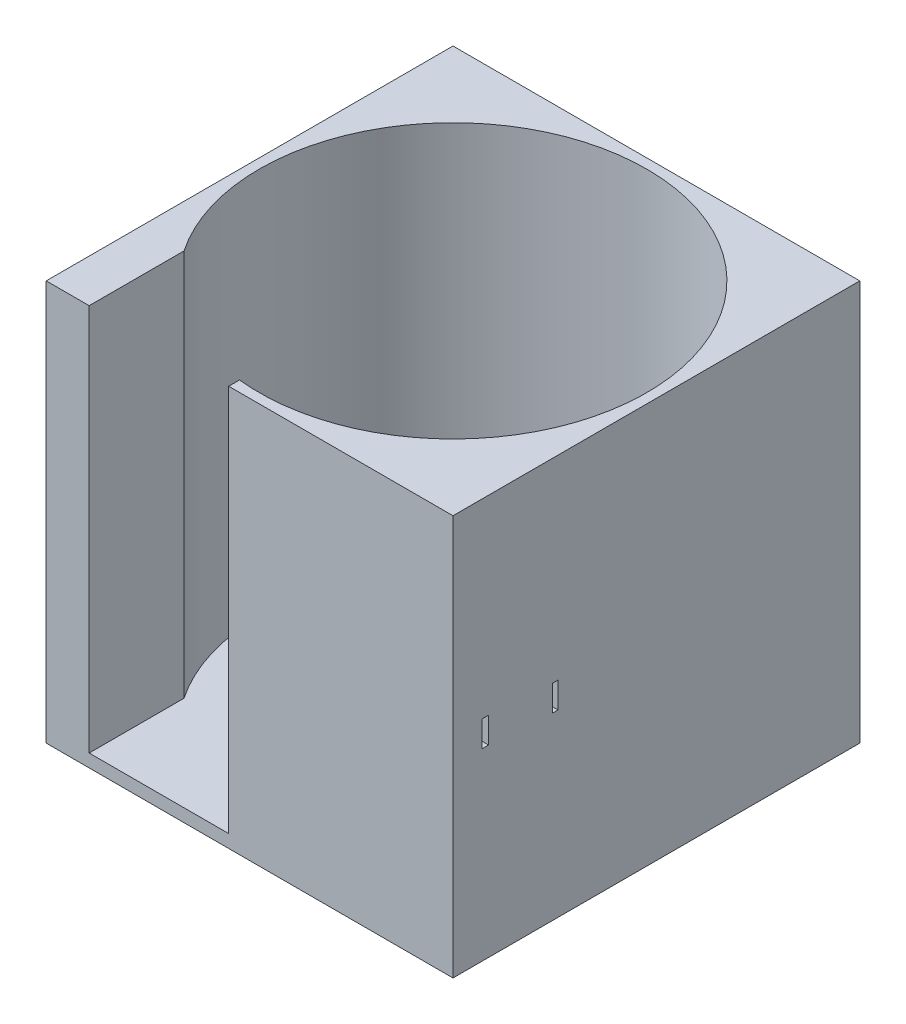
SolidWorks part; units mm, degrees
ref_plane "Front Plane" through (0, 0, 0) normal (0, 0, 1) x (1, 0, 0)
ref_plane "Top Plane" through (0, 0, 0) normal (0, 1, 0) x (1, 0, 0)
ref_plane "Right Plane" through (0, 0, 0) normal (1, 0, 0) x (0, 0, -1)
sketch "Sketch1" plane through (0, 0, 0) normal (0, 1, 0) x (1, 0, 0)
  line L1 (-31.5, -31.5) -> (31.5, -31.5)
  line L2 (-31.5, -31.5) -> (-31.5, 31.5)
  line L3 (-31.5, 31.5) -> (31.5, 31.5)
  line L4 (31.5, -31.5) -> (31.5, 31.5)
  line L5 (-31.5, -31.5) -> (31.5, 31.5) construction
  line L6 (-31.5, 31.5) -> (31.5, -31.5) construction
  point P0 (0, 0)
  dimension "D1" = 63
  dimension "D2" = 63
extrude "Boss-Extrude1" add sketch "Sketch1" along normal blind 62
sketch "Sketch2" plane through (0, 62, 0) normal (0, 1, 0) x (1, 0, 0)
  circle A0 centre (0, 0) radius 30
  dimension "D1" = 60
extrude "Cut-Extrude1" cut sketch "Sketch2" against normal blind 60
sketch "Sketch4" plane through (0, 2, 0) normal (0, 1, 0) x (1, 0, 0)
  circle A0 centre (0, 0) radius 5
  dimension "D1" = 10
extrude "Cut-Extrude2" cut sketch "Sketch4" against normal through all
sketch "Sketch17" plane through (0, 62, 0) normal (0, 1, 0) x (1, 0, 0)
  line L0 (-31.5, -31.5) -> (31.5, -31.5) construction
  line L1 (-3.235, -31.5) -> (-24.8473, -31.5)
  line L2 (-3.235, -31.5) -> (-3.235, -16.811)
  line L3 (-3.235, -16.811) -> (-24.8473, -16.811)
  line L4 (-24.8473, -31.5) -> (-24.8473, -16.811)
  circle A0 centre (0, 0) radius 30 construction
extrude "Cut-Extrude10" cut sketch "Sketch17" against normal blind 60
sketch "Sketch7" plane through (0, 2, 0) normal (0, 1, 0) x (1, 0, 0)
  text T0 "Evening" font "@Microsoft YaHei UI" height 3.5
sketch "Sketch9" plane through (0, 2, 0) normal (0, 1, 0) x (1, 0, 0)
  text T0 "Morning" font "@Microsoft YaHei" height 3.5
extrude "Cut-Extrude5" cut sketch "Sketch9" against normal blind 0.5
sketch "Sketch8" plane through (0, 2, 0) normal (0, 1, 0) x (1, 0, 0)
  text T0 "Noon" font "@Microsoft YaHei" height 3.5
extrude "Cut-Extrude6" cut sketch "Sketch8" against normal blind 0.5
extrude "Cut-Extrude7" cut sketch "Sketch7" against normal blind 0.5
sketch "Sketch19" plane through (31.5, 0, 0) normal (1, 0, 0) x (0, 0, -1)
  line L0 (-31.5, 0) -> (-16, 0) construction
  line L1 (-31.5, 0) -> (31.5, 0) construction
  line L4 (-16.1198, 31.8299) -> (-15.25, 31.8299)
  line L5 (-16.1198, 31.8299) -> (-16.1198, 27.8299)
  line L6 (-16.1198, 27.8299) -> (-15.25, 27.8299)
  line L7 (-15.25, 31.8299) -> (-15.25, 27.8299)
  line L8 (-16.1198, 31.8299) -> (-15.25, 27.8299) construction
  line L9 (-16.1198, 27.8299) -> (-15.25, 31.8299) construction
  dimension "D3" = 4
  dimension "D4" = 0.8698
extrude "Cut-Extrude11" cut sketch "Sketch19" against normal blind 10
sketch "Sketch21" plane through (0, 0, 0) normal (1, 0, 0) x (0, 0, -1)
  line L0 (-30.6333, 29.2692) -> (-14.8833, 29.2692) construction
  line L2 (-16.3833, 27.7692) -> (-13.3833, 27.7692)
  line L3 (-16.3833, 27.7692) -> (-16.3833, 30.7692)
  line L4 (-16.3833, 30.7692) -> (-13.3833, 30.7692)
  line L5 (-13.3833, 27.7692) -> (-13.3833, 30.7692)
  line L6 (-16.3833, 27.7692) -> (-13.3833, 30.7692) construction
  line L7 (-16.3833, 30.7692) -> (-13.3833, 27.7692) construction
  point P6 (0, 0)
  point P7 (0, 0)
  point P8 (0, 0)
  dimension "D1" = 15.75
  dimension "D2" = 3
  dimension "D3" = 3
extrude "Cut-Extrude17" cut sketch "Sketch21" along normal blind 27.5
sketch "Sketch25" plane through (31.5, 0, 0) normal (1, 0, 0) x (0, 0, -1)
  line L0 (-31.5, 62) -> (-31.5, 30.5) construction
  line L1 (-31.5, 62) -> (-31.5, 0) construction
  line L2 (-31.5, 30.5) -> (-26.5, 30.5) construction
  line L4 (-27, 32.5) -> (-26, 32.5)
  line L5 (-27, 32.5) -> (-27, 28.5)
  line L6 (-27, 28.5) -> (-26, 28.5)
  line L7 (-26, 32.5) -> (-26, 28.5)
  line L8 (-27, 32.5) -> (-26, 28.5) construction
  line L9 (-27, 28.5) -> (-26, 32.5) construction
  dimension "D1" = 31.5
  dimension "D2" = 5
  dimension "D3" = 4
  dimension "D4" = 1
extrude "Cut-Extrude21" cut sketch "Sketch25" against normal blind 5
sketch "Sketch29" plane through (0, 0, 0) normal (0, -1, 0) x (1, 0, 0)
  line L0 (31.5, 31.5) -> (26.5, 31.5) construction
  line L1 (-31.5, 31.5) -> (31.5, 31.5) construction
  line L2 (26.5, 31.5) -> (26.5, 26.5) construction
  circle A0 centre (26.5, 26.5) radius 3.05
  dimension "D3" = 6.1
  dimension "D1" = 5
  dimension "D2" = 5
extrude "Cut-Extrude25" cut sketch "Sketch29" against normal blind 8.5
sketch "Sketch30" plane through (0, 0, 0) normal (0, -1, 0) x (1, 0, 0)
  circle A0 centre (26.5, 26.5) radius 2
  dimension "D1" = 4
extrude "Cut-Extrude26" cut sketch "Sketch30" against normal blind 32.5
